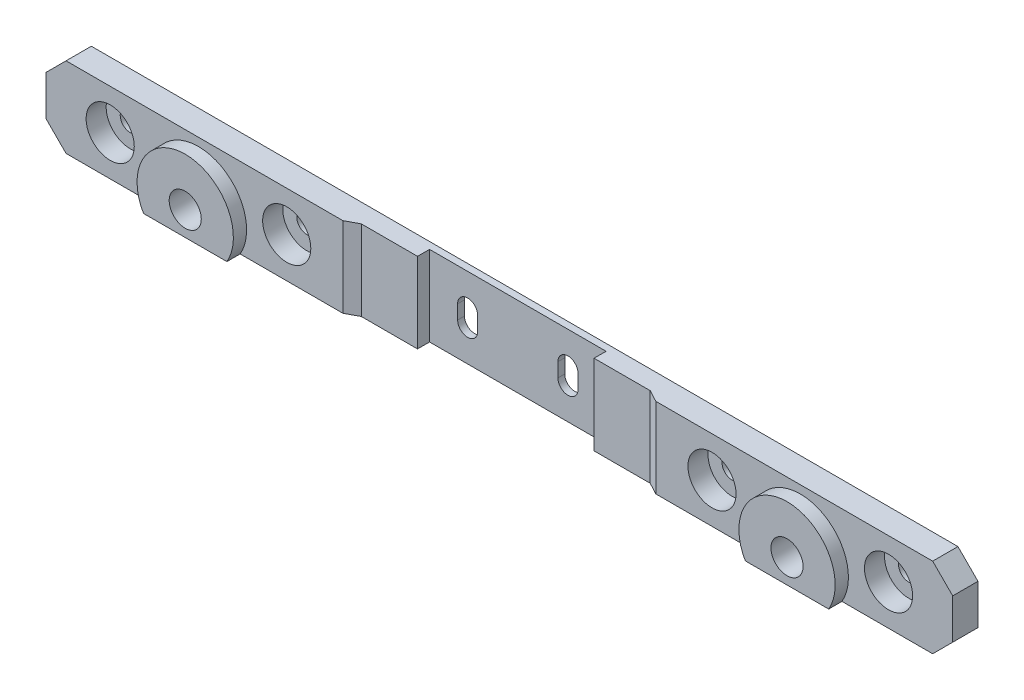
SolidWorks part; units mm, degrees
ref_plane "Front Plane" through (0, 0, 0) normal (0, 0, 1) x (1, 0, 0)
ref_plane "Top Plane" through (0, 0, 0) normal (0, 1, 0) x (1, 0, 0)
ref_plane "Right Plane" through (0, 0, 0) normal (1, 0, 0) x (0, 0, -1)
sketch "Sketch1" plane through (0, 0, 0) normal (0, 0, 1) x (1, 0, 0)
  line L0 (113, 0) -> (113, -20) construction
  line L1 (0, 0) -> (226, 0)
  line L2 (0, 0) -> (0, -20)
  line L3 (0, -20) -> (226, -20)
  line L4 (226, 0) -> (226, -20)
  line L5 (5, 0) -> (0, -5)
  line L6 (0, -15) -> (5, -20)
  line L7 (0, -10) -> (50000, -10) construction
  line L12 (226, -10) -> (-49774, -10) construction
  line L13 (98, -5.75) -> (103, -5.75)
  line L14 (98, -5.75) -> (98, -14.25)
  line L15 (98, -14.25) -> (103, -14.25)
  line L16 (103, -5.75) -> (103, -14.25)
  line L17 (123, -5.75) -> (123, -14.25)
  line L18 (128, -14.25) -> (123, -14.25)
  line L19 (128, -5.75) -> (128, -14.25)
  line L20 (128, -5.75) -> (123, -5.75)
  line L21 (226, -15) -> (221, -20)
  line L22 (221, 0) -> (226, -5)
  line L23 (226, 0) -> (226, -20)
  line L24 (0, -10) -> (50000, -10) construction
  line L25 (226, -10) -> (-49774, -10) construction
  circle A1 centre (16, -10) radius 2.5
  circle A2 centre (60, -10) radius 2.5
  circle A3 centre (100.5, -8.25) radius 2.5
  circle A4 centre (100.5, -11.75) radius 2.5
  circle A5 centre (125.5, -11.75) radius 2.5
  circle A6 centre (125.5, -8.25) radius 2.5
  circle A7 centre (166, -10) radius 2.5
  circle A8 centre (210, -10) radius 2.5
  circle A10 centre (38, -14) radius 4
  circle A11 centre (188, -14) radius 4
  point P13 (0, -10)
  dimension "D7" = 5
  dimension "D13" = 2.5
  dimension "D17" = 8
  dimension "D1" = 226
  dimension "D2" = 20
  dimension "D3" = 5
  dimension "D4" = 5
  dimension "D5" = 5
  dimension "D6" = 5
  dimension "D8" = 16
  dimension "D9" = 44
  dimension "D10" = 98
  dimension "D11" = 5
  dimension "D12" = 8.5
  dimension "D14" = 2.5
  dimension "D15" = 2.5
  dimension "D16" = 2.5
  dimension "D18" = 6
  dimension "D19" = 38
extrude "Boss-Extrude1" add sketch "Sketch1" along normal blind 9.6 contours L22 L1 L5 L2 L6 L3 L21 L4 A7 A2 A1 L20 L19 L18 L17 L13 L16 L15 L14 A8 | A3 L13 L14 | A3 L16 L13 | A4 L15 L16 | L17 A6 L20 | A4 L14 L15 | L20 A6 L19 | L19 A5 L18 | L18 A5 L17
sketch "Sketch2" plane through (0, 0, 9.6) normal (0, 0, 1) x (1, 0, 0)
  line L0 (113, -20) -> (113, 49980) construction
  line L1 (5, -20) -> (221, -20) construction
  line L2 (221, 0) -> (226, -5)
  line L3 (221, 0) -> (226, -5)
  line L4 (226, -5) -> (226, -15)
  line L5 (226, -5) -> (226, -15)
  line L6 (226, -15) -> (221, -20)
  line L7 (226, -15) -> (221, -20)
  line L8 (221, -20) -> (5, -20)
  line L9 (221, -20) -> (5, -20)
  line L10 (5, -20) -> (0, -15)
  line L11 (5, -20) -> (0, -15)
  line L12 (0, -15) -> (0, -5)
  line L13 (0, -15) -> (0, -5)
  line L14 (0, -5) -> (5, 0)
  line L15 (0, -5) -> (5, 0)
  line L16 (5, 0) -> (221, 0)
  line L17 (5, 0) -> (221, 0)
  circle A0 centre (38, -14) radius 12
  circle A1 centre (188, -14) radius 12
  point P7 (113, -20)
  arc M3 (98, -8.25) -> (103, -8.25) centre (100.5, -8.25) cw
  line M4 (103, -8.25) -> (103, -11.75)
  arc M5 (103, -11.75) -> (98, -11.75) centre (100.5, -11.75) cw
  line M6 (98, -11.75) -> (98, -8.25)
  arc M7 (123, -8.25) -> (128, -8.25) centre (125.5, -8.25) cw
  line M8 (128, -8.25) -> (128, -11.75)
  arc M9 (128, -11.75) -> (123, -11.75) centre (125.5, -11.75) cw
  line M10 (123, -11.75) -> (123, -8.25)
  circle M11 centre (210, -10) radius 2.5
  line M12 (226, -5) -> (221, 0)
  line M13 (221, 0) -> (5, 0)
  line M14 (5, 0) -> (0, -5)
  line M15 (0, -5) -> (0, -15)
  line M16 (0, -15) -> (5, -20)
  line M17 (5, -20) -> (221, -20)
  line M18 (221, -20) -> (226, -15)
  line M19 (226, -15) -> (226, -5)
  circle M20 centre (16, -10) radius 2.5
  circle M21 centre (60, -10) radius 2.5
  circle M22 centre (166, -10) radius 2.5
  dimension "D1" = 24
extrude "Cut-Extrude1" cut sketch "Sketch2" against normal blind 3.3 contours L0 L17 A0 M17 M14 M15 M16 M21 M20 M6 M3 M4 M5 | L0 L9 A1 M17 M18 M19 M12 M13 M10 M7 M8 M9 M11 M22
sketch "Sketch4" plane through (0, -20, 0) normal (0, -1, 0) x (1, 0, 0)
  line L0 (113, 6.3) -> (113, 50006.3) construction
  line L1 (48.3923, 6.3) -> (177.6077, 6.3) construction
  line L2 (176, 9.6) -> (199.9997, 9.6)
  line L3 (176, 9.6) -> (199.9997, 9.6)
  line L4 (199.9997, 9.6) -> (199.9997, 6.3)
  line L5 (199.9997, 9.6) -> (199.9997, 6.3)
  line L6 (199.9997, 6.3) -> (221, 6.3)
  line L7 (199.9997, 6.3) -> (221, 6.3)
  line L8 (221, 6.3) -> (226, 6.3)
  line L9 (221, 6.3) -> (226, 6.3)
  line L10 (226, 6.3) -> (226, 0)
  line L11 (226, 6.3) -> (226, 0)
  line L12 (226, 0) -> (221, 0)
  line L13 (226, 0) -> (221, 0)
  line L14 (221, 0) -> (5, 0)
  line L15 (221, 0) -> (5, 0)
  line L16 (5, 0) -> (0, 0)
  line L17 (5, 0) -> (0, 0)
  line L18 (0, 0) -> (0, 6.3)
  line L19 (0, 0) -> (0, 6.3)
  line L20 (0, 6.3) -> (5, 6.3)
  line L21 (0, 6.3) -> (5, 6.3)
  line L22 (5, 6.3) -> (26, 6.3)
  line L23 (5, 6.3) -> (26, 6.3)
  line L24 (26, 6.3) -> (26, 9.6)
  line L25 (26, 6.3) -> (26, 9.6)
  line L26 (26, 9.6) -> (49.9997, 9.6)
  line L27 (26, 9.6) -> (49.9997, 9.6)
  line L28 (49.9997, 9.6) -> (49.9997, 6.3)
  line L29 (49.9997, 9.6) -> (49.9997, 6.3)
  line L30 (49.9997, 6.3) -> (176, 6.3)
  line L31 (49.9997, 6.3) -> (74, 6.3)
  line L32 (176, 6.3) -> (176, 9.6)
  line L33 (176, 6.3) -> (176, 9.6)
  line L34 (74, 6.3) -> (77, 4.7)
  line L35 (77, 4.7) -> (91, 4.7)
  line L36 (91, 4.7) -> (91, 1.7)
  line L37 (91, 1.7) -> (135, 1.7)
  line L38 (135, 4.7) -> (135, 1.7)
  line L39 (149, 4.7) -> (135, 4.7)
  line L40 (152, 6.3) -> (149, 4.7)
  line L41 (176.0003, 6.3) -> (152, 6.3)
  line L42 (176.0003, 9.6) -> (176.0003, 6.3)
  line L43 (200, 9.6) -> (176.0003, 9.6)
  line L44 (200, 6.3) -> (200, 9.6)
  line L45 (221, 6.3) -> (200, 6.3)
  line L46 (226, 6.3) -> (221, 6.3)
  line L47 (226, 0) -> (226, 6.3)
  line L48 (221, 0) -> (226, 0)
  line L49 (152, 6.3) -> (176, 6.3)
  line L50 (74, 6.3) -> (50, 6.3)
  point P4 (113, 6.3)
  point P27 (113, 1.7)
  line M27 (177.6077, 6.3) -> (48.3923, 6.3)
  dimension "D1" = 74
  dimension "D2" = 1.6
  dimension "D3" = 3
  dimension "D4" = 14
  dimension "D5" = 3
extrude "Cut-Extrude2" cut sketch "Sketch4" against normal through all contours L37 L0 L34 L35 L36 M27 | L0 L37 L38 L39 L40 M27
sketch "Sketch5" plane through (0, 0, 6.3) normal (0, 0, 1) x (1, 0, 0)
  circle A0 centre (16, -10) radius 6
  circle A1 centre (60, -10) radius 6
  circle A2 centre (166, -10) radius 6
  circle A3 centre (210, -10) radius 6
  dimension "D1" = 12
extrude "Cut-Extrude3" cut sketch "Sketch5" against normal blind 5
